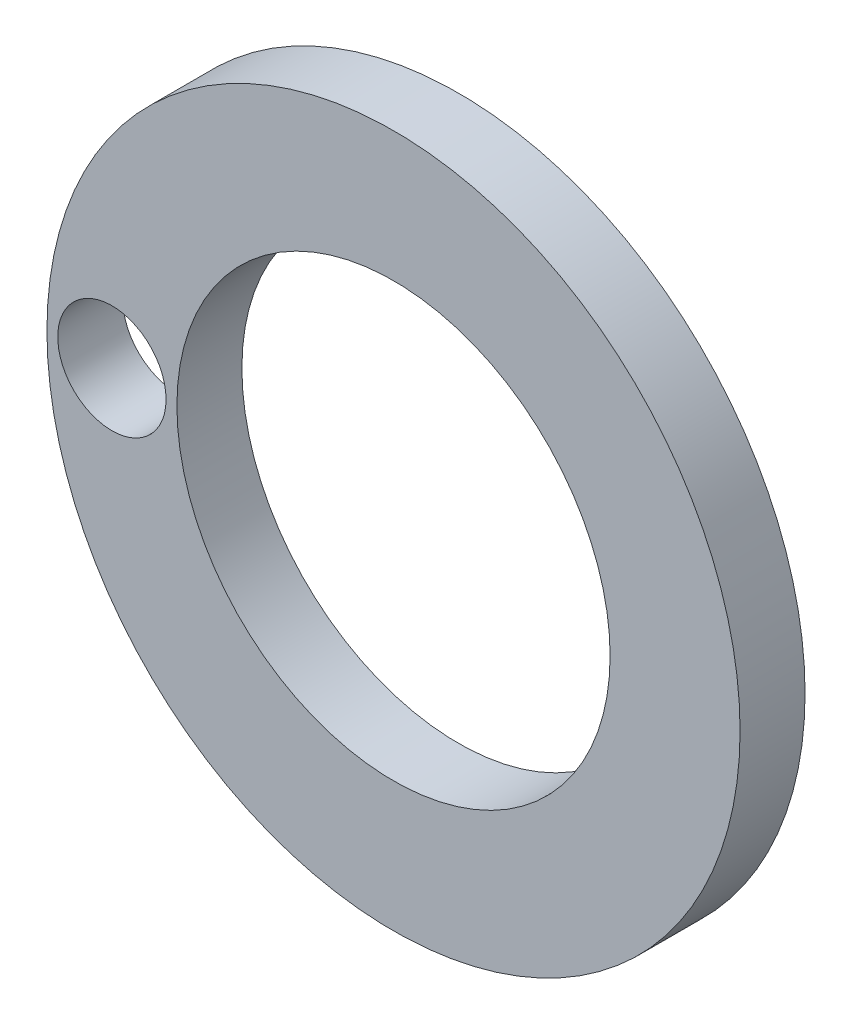
SolidWorks part; units mm, degrees
ref_plane "Front Plane" through (0, 0, 0) normal (0, 0, 1) x (1, 0, 0)
ref_plane "Top Plane" through (0, 0, 0) normal (0, 1, 0) x (1, 0, 0)
ref_plane "Right Plane" through (0, 0, 0) normal (1, 0, 0) x (0, 0, -1)
sketch "Sketch1" plane through (0, 0, 0) normal (0, 0, 1) x (1, 0, 0)
  circle A0 centre (0, 0) radius 10
  circle A1 centre (0, 0) radius 16
  circle A4 centre (-13, 0) radius 2.5
  dimension "D1" = 20
  dimension "D2" = 32
  dimension "D3" = 5
extrude "Boss-Extrude1" add sketch "Sketch1" along normal blind 3
scale "Scale1" scale about centroid uniform scaling yes scale factor 1.9329
scale "Scale2" scale about centroid uniform scaling yes scale factor 1.5
